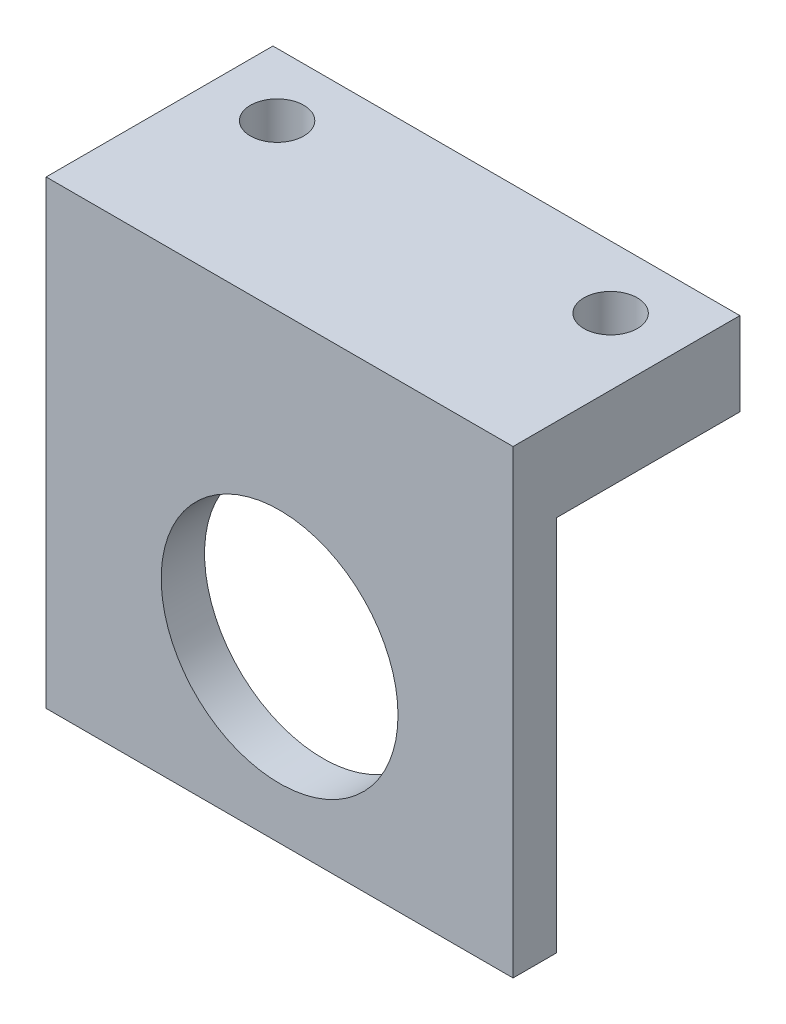
SolidWorks part; units mm, degrees
ref_plane "Front Plane" through (0, 0, 0) normal (0, 0, 1) x (1, 0, 0)
ref_plane "Top Plane" through (0, 0, 0) normal (0, 1, 0) x (1, 0, 0)
ref_plane "Right Plane" through (0, 0, 0) normal (1, 0, 0) x (0, 0, -1)
sketch "Sketch11" plane through (0, 0, 0) normal (0, 1, 0) x (1, 0, 0)
  line L0 (17.78, 0) -> (17.78, 6.7945) construction
  line L1 (0, 0) -> (35.56, 0)
  line L2 (0, 0) -> (0, 32.385)
  line L3 (0, 32.385) -> (35.56, 32.385)
  line L4 (35.56, 0) -> (35.56, 32.385)
  line L5 (0, 32.385) -> (3.048, 32.385) construction
  line L6 (0, 32.385) -> (0, 27.6053) construction
  line L9 (35.56, 32.385) -> (22.352, 32.385) construction
  line L10 (35.56, 32.385) -> (35.56, 29.6545) construction
  line L13 (17.78, 6.7945) -> (17.78, 27.6225) construction
  line L14 (17.78, 27.6225) -> (5.08, 27.6225) construction
  line L15 (17.78, 27.6225) -> (30.48, 27.6225) construction
  circle A0 centre (5.08, 27.6225) radius 2.032
  circle A1 centre (30.48, 27.6225) radius 2.032
  circle A2 centre (17.78, 6.7945) radius 2.032
  dimension "D5" = 4.064
  dimension "D8" = 4.064
  dimension "D10" = 4.064
  dimension "D2" = 4.7625
  dimension "D3" = 5.08
  dimension "D9" = 6.7945
  dimension "D11" = 20.828
  dimension "D12" = 12.7
  dimension "D13" = 12.7
extrude "Boss-Extrude1" add sketch "Sketch11" along normal blind 6.35
sketch "Sketch12" plane through (0, 6.35, 0) normal (0, 1, 0) x (1, 0, 0)
  line L0 (17.78, 0) -> (17.78, 13.1445) construction
  line L1 (0, 0) -> (35.56, 0) construction
  line L2 (0, 32.385) -> (0, 0) construction
  line L3 (0, 13.1445) -> (35.56, 13.1445)
  line L4 (0, 13.1445) -> (0, 17.2085)
  line L5 (0, 17.2085) -> (35.56, 17.2085)
  line L6 (35.56, 13.1445) -> (35.56, 17.2085)
  line L7 (35.56, 0) -> (35.56, 32.385) construction
  dimension "D1" = 13.1445
  dimension "D2" = 4.064
sketch "Sketch14" plane through (0, 0, 0) normal (0, -1, 0) x (1, 0, 0)
  line L0 (17.78, -32.385) -> (17.78, -18.415) construction
  line L1 (35.56, -32.385) -> (0, -32.385) construction
  line L2 (35.56, 0) -> (35.56, -32.385) construction
  line L3 (35.56, -18.415) -> (0, -18.415)
  line L4 (35.56, -18.415) -> (35.56, -15.113)
  line L5 (35.56, -15.113) -> (0, -15.113)
  line L6 (0, -18.415) -> (0, -15.113)
  line L8 (0, -32.385) -> (0, 0) construction
  point P12 (17.78, -18.415)
  dimension "D1" = 13.97
  dimension "D2" = 3.302
extrude "Boss-Extrude2" add sketch "Sketch14" along normal blind 28.702
sketch "Sketch15" plane through (0, 0, -15.113) normal (0, 0, 1) x (1, 0, 0)
  line L0 (17.78, -28.702) -> (17.78, -15.748) construction
  line L1 (35.56, -28.702) -> (0, -28.702) construction
  circle A0 centre (17.78, -15.748) radius 9.017
  dimension "D2" = 18.034
  dimension "D1" = 12.954
extrude "Cut-Extrude1" cut sketch "Sketch15" against normal up to next
sketch "Sketch16" plane through (0, 0, 0) normal (0, -1, 0) x (1, 0, 0)
  line L1 (35.56, -15.113) -> (0, -15.113)
  line L2 (35.56, -15.113) -> (35.56, 0)
  line L3 (35.56, 0) -> (0, 0)
  line L4 (0, -15.113) -> (0, 0)
extrude "Cut-Extrude2" cut sketch "Sketch16" against normal through all
